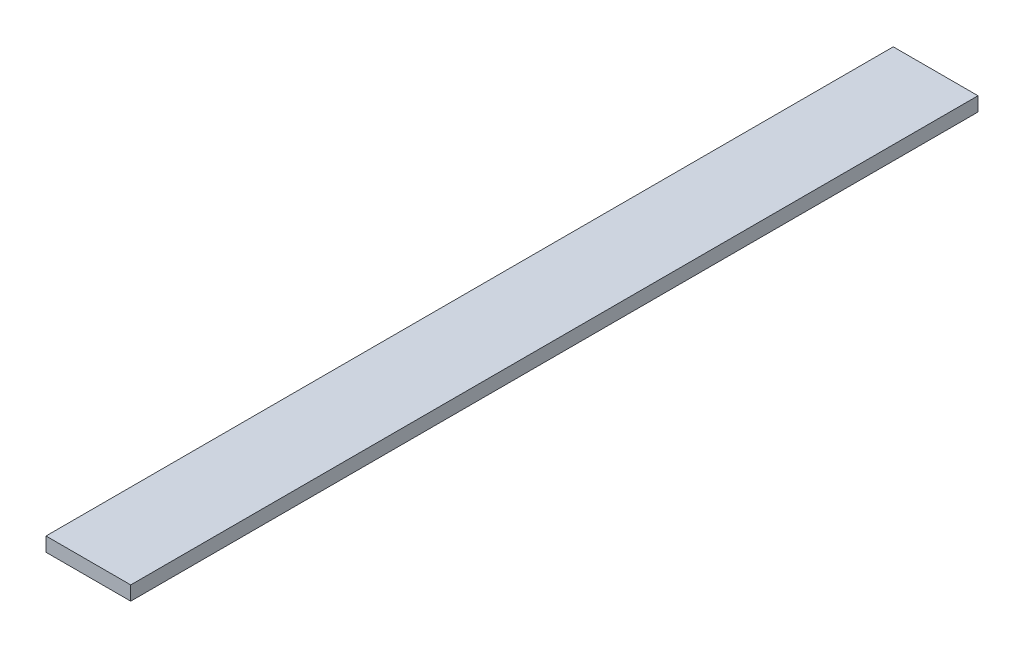
SolidWorks part; units mm, degrees
ref_plane "Front Plane" through (0, 0, 0) normal (0, 0, 1) x (1, 0, 0)
ref_plane "Top Plane" through (0, 0, 0) normal (0, 1, 0) x (1, 0, 0)
ref_plane "Right Plane" through (0, 0, 0) normal (1, 0, 0) x (0, 0, -1)
sketch "Sketch1" plane through (0, 0, 0) normal (0, 1, 0) x (1, 0, 0)
  line L1 (15, 150) -> (-15, 150)
  line L2 (15, 150) -> (15, -150)
  line L3 (15, -150) -> (-15, -150)
  line L4 (-15, 150) -> (-15, -150)
  line L5 (15, 150) -> (-15, -150) construction
  line L6 (15, -150) -> (-15, 150) construction
  point P0 (0, 0)
  dimension "D1" = 300
  dimension "D2" = 30
extrude "Boss-Extrude1" add sketch "Sketch1" along normal blind 5
